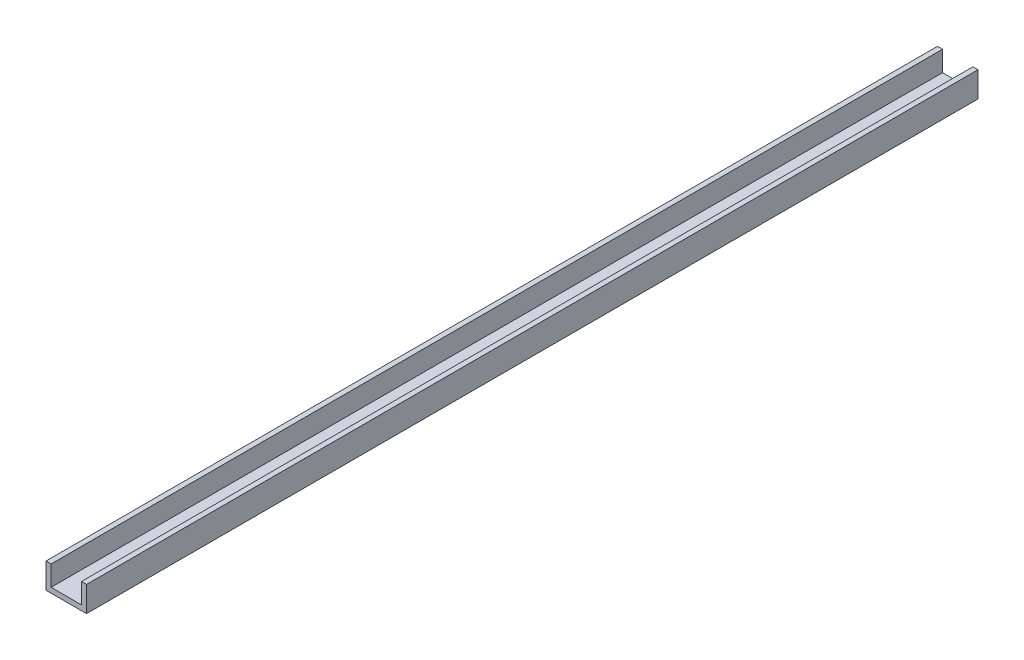
SolidWorks part; units mm, degrees
ref_plane "Front" through (0, 0, 0) normal (0, 0, 1) x (1, 0, 0)
ref_plane "Top" through (0, 0, 0) normal (0, 1, 0) x (1, 0, 0)
ref_plane "Right" through (0, 0, 0) normal (1, 0, 0) x (0, 0, -1)
sketch "Sketch1" plane through (0, 0, 0) normal (0, 0, 1) x (1, 0, 0)
  line L0 (0, -3.9688) -> (0, 3.9688) construction
  line L1 (-6.35, 0) -> (6.35, 0) construction
  line L2 (4.7625, 3.9688) -> (-4.7625, 3.9688) construction
  line L3 (-6.35, -3.9688) -> (6.35, -3.9688)
  line L4 (-6.35, -3.9688) -> (-6.35, 3.9688)
  line L5 (-6.35, 3.9688) -> (6.35, 3.9688)
  line L6 (6.35, -3.9688) -> (6.35, 3.9688)
  line L7 (-6.35, -3.9688) -> (6.35, 3.9688) construction
  line L8 (-6.35, 3.9688) -> (6.35, -3.9688) construction
  line L9 (-4.7625, -3.9688) -> (4.7625, -3.9688)
  point P3 (0, 0)
  point P4 (0, 0)
  point P8 (0, 0)
  point P13 (6.35, -2.3812)
  point P17 (0, 3.9688)
  point P20 (0, -3.9688)
  dimension "Outside Width" = 12.7
  dimension "Outside Height" = 7.9375
  dimension "Inside Height" = 6.35
  dimension "Wall Thickness" = 1.5875
  dimension "Inside Width" = 9.525
sketch "Sketch2" plane through (0, 0, 0) normal (1, 0, 0) x (0, 0, -1)
  line L0 (-609.6, 0) -> (609.6, 0) construction
  dimension "Length" = 1219.2
sketch "Sketch3" plane through (0, 0, 0) normal (0, 0, 1) x (1, 0, 0)
  line L0 (-6.35, 3.9688) -> (-6.35, -3.9687)
  line L1 (-6.35, -3.9687) -> (6.35, -3.9687)
  line L2 (6.35, -3.9687) -> (6.35, 3.9688)
  line L3 (6.35, 3.9688) -> (4.7625, 3.9688)
  line L4 (4.7625, 3.9688) -> (4.7625, -2.3812)
  line L5 (4.7625, -2.3812) -> (-4.7625, -2.3812)
  line L6 (-4.7625, -2.3812) -> (-4.7625, 3.9688)
  line L7 (-4.7625, 3.9688) -> (-6.35, 3.9688)
  line L8 (-4.7625, -2.3812) -> (-4.7625, -3.9687) construction
  dimension "D1" = 7.9375
  dimension "D2" = 12.7
  dimension "D3" = 1.5875
extrude "Boss-Extrude2" add sketch "Sketch3" along normal mid plane 1219.2
sketch "Reference Sketch1" plane through (0, 0, 0) normal (1, 0, 0) x (0, 0, -1)
  line L0 (-609.6, 0) -> (609.6, 0) construction
  point P0 (-595.7094, 0)
  point P1 (595.7094, 0)
  dimension "D1" = 13.8906
  dimension "D2" = 13.8906
sketch "Sketch4" plane through (0, 0, -609.6) normal (0, 0, 1) x (1, 0, 0)
  line L1 (-8.7156, -6.6556) -> (8.7156, -6.6556)
  line L2 (-8.7156, -6.6556) -> (-8.7156, 6.6556)
  line L3 (-8.7156, 6.6556) -> (8.7156, 6.6556)
  line L4 (8.7156, -6.6556) -> (8.7156, 6.6556)
  line L5 (-8.7156, -6.6556) -> (8.7156, 6.6556) construction
  line L6 (-8.7156, 6.6556) -> (8.7156, -6.6556) construction
  point P0 (0, 0)
extrude "Cut-Extrude1" cut sketch "Sketch4" along normal offset from surface (939.8 mm away) 279.4 up to face at (0, 0.3969, 609.6)
sketch "Sketch5" plane through (0, -3.9687, 0) normal (0, -1, 0) x (1, 0, 0)
  line L0 (-6.35, 609.6) -> (6.35, 609.6) construction
  circle A0 centre (0, 584.2) radius 1.5875
  dimension "D1" = 25.4
  dimension "D2" = 3.175
extrude "Cut-Extrude2" cut sketch "Sketch5" against normal through all
chamfer "Chamfer1" distance 1.27 angle 45 1 edges at (0, -3.9687, 582.6125)
equation "\"D1@Sketch3\" = \"Outside Height@Sketch1\""
equation "\"D2@Sketch3\" = \"Outside Width@Sketch1\""
equation "\"D3@Sketch3\" = \"Wall Thickness@Sketch1\""
equation "\"D1@Reference Sketch1\"=\"Outside Height@Sketch1\" * 1.75"
equation "\"D2@Reference Sketch1\" = \"D1@Reference Sketch1\""
equation "\"D1@Boss-Extrude2\" = \"Length@Sketch2\""
equation "\"Inside Height@Sketch1\"=\"Outside Height@Sketch1\"-\"Wall Thickness@Sketch1\""
equation "\"Inside Width@Sketch1\"=\"Outside Width@Sketch1\"-\"Wall Thickness@Sketch1\"*2"
